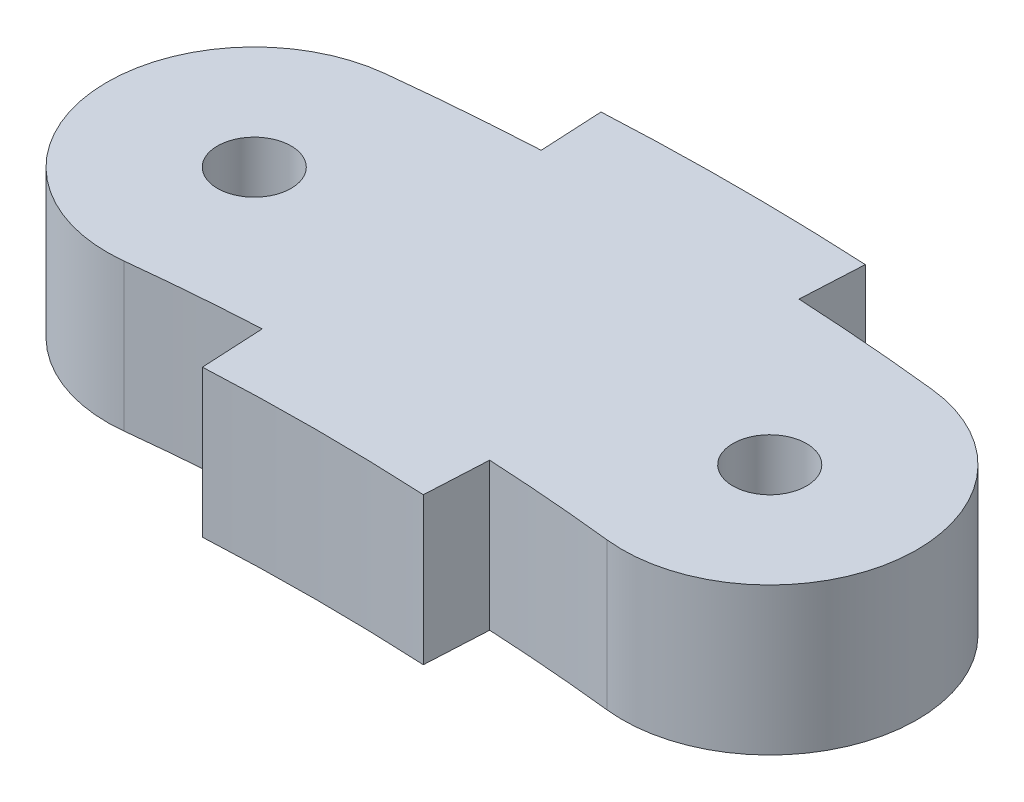
SolidWorks part; units mm, degrees
ref_plane "Front Plane" through (0, 0, 0) normal (0, 0, 1) x (1, 0, 0)
ref_plane "Top Plane" through (0, 0, 0) normal (0, 1, 0) x (1, 0, 0)
ref_plane "Right Plane" through (0, 0, 0) normal (1, 0, 0) x (0, 0, -1)
sketch "Sketch1" plane through (0, 0, 0) normal (0, 1, 0) x (1, 0, 0)
  line L0 (-7.5, -0.1934) -> (-8.9727, 28.3436)
  line L1 (7.5, -0.1934) -> (8.9727, 28.3436)
  arc A0 (-8.9727, 28.3436) -> (8.9727, 28.3436) centre (0, -145.5262) cw
  arc A1 (-7.5, -0.1934) -> (7.5, -0.1934) centre (0, -145.5262) cw
  dimension "D1" = 28.575
  dimension "D2" = 145.5262
  dimension "D3" = 15
extrude "Boss-Extrude1" add sketch "Sketch1" along normal mid plane 10
sketch "Sketch2" plane through (0, 5, 0) normal (0, 1, 0) x (1, 0, 0)
  line L0 (0, 0) -> (0, 28.575) construction
  arc A0 (-17.5, 13.3265) -> (17.5, 13.3265) centre (0, -145.5262) cw construction
  arc A1 (7.5, -0.1934) -> (-7.5, -0.1934) centre (0, -145.5262) ccw construction
  arc A2 (8.9727, 28.3436) -> (-8.9727, 28.3436) centre (0, -145.5262) ccw construction
  arc A3 (-16.405, 3.3866) -> (16.405, 3.3866) centre (0, -145.5262) cw
  arc A4 (-18.595, 23.2663) -> (18.595, 23.2663) centre (0, -145.5262) cw
  arc A5 (-16.405, 3.3866) -> (-18.595, 23.2663) centre (-17.5, 13.3265) cw
  arc A6 (16.405, 3.3866) -> (18.595, 23.2663) centre (17.5, 13.3265) ccw
  point P11 (0, 14.2875)
  dimension "D1" = 35
  dimension "D2" = 10
  dimension "D3" = 10
extrude "Boss-Extrude2" add sketch "Sketch2" against normal through all
hole_wizard "M6x1.0 Tapped Hole1" positions "Sketch3" profile "Sketch4" tap size "M6x1.0" standard "ANSI Metric" end condition through all
sketch "Sketch3" plane through (0, 5, 0) normal (0, 1, 0) x (1, 0, 0)
  point P0 (-17.5, 13.3265)
  point P3 (17.5, 13.3265)
sketch "Sketch4" plane through (-17.5, 5, -13.3265) normal (1, 0, 0) x (0, 0, 1)
  line L0 (0, 0) -> (0, 10)
  line L1 (0, 10) -> (2.5, 10)
  line L2 (2.5, 10) -> (2.5, 0)
  line L5 (2.5, 0) -> (0, 0)
  line L11 (0, -6.35) -> (0, 107.95) construction
  dimension "Thru Tap Drill Dia." = 5
  dimension "Thru Tap Drill Depth" = 10
cosmetic thread "Hole Thread1" parameters "D2"=6
cosmetic thread "Hole Thread2" parameters "D2"=6
sketch "Sketch8" plane through (0, 0, 0) normal (0, 0, 1) x (1, 0, 0)
  circle A0 centre (0, 0) radius 2.5
  dimension "D1" = 5
extrude "Cut-Extrude1" cut sketch "Sketch8" against normal blind 20 from offset 10
